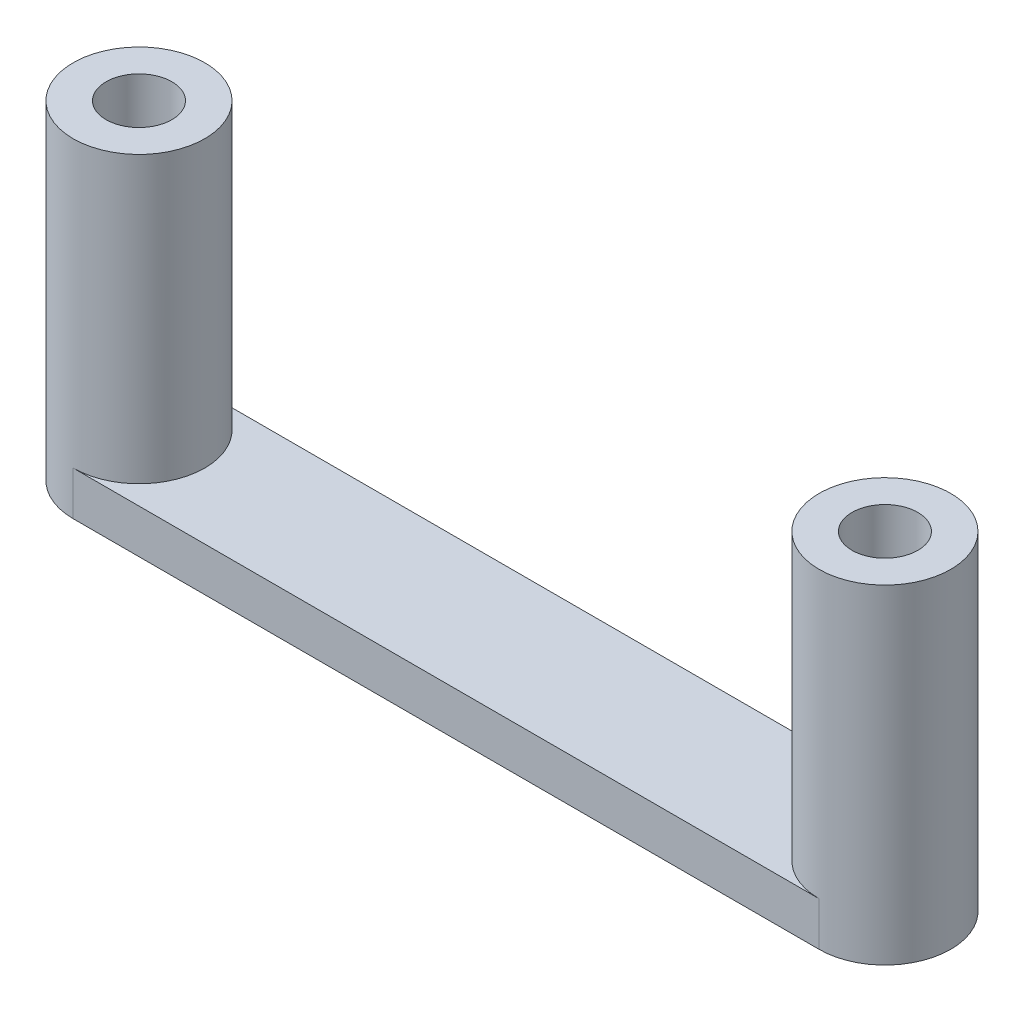
SolidWorks part; units mm, degrees
ref_plane "前视基准面" through (0, 0, 0) normal (0, 0, 1) x (1, 0, 0)
ref_plane "上视基准面" through (0, 0, 0) normal (0, 1, 0) x (1, 0, 0)
ref_plane "右视基准面" through (0, 0, 0) normal (1, 0, 0) x (0, 0, -1)
other "Configuration Table"
sketch "草图1" plane through (0, 0, 0) normal (0, 1, 0) x (1, 0, 0)
  line L0 (-15.9188, 0) -> (18.0812, 0) construction
  line L1 (-15.9188, 3) -> (18.0812, 3)
  line L2 (-15.9188, -3) -> (18.0812, -3)
  arc A0 (-15.9188, 3) -> (-15.9188, -3) centre (-15.9188, 0) ccw
  arc A1 (18.0812, -3) -> (18.0812, 3) centre (18.0812, 0) ccw
  point P3 (1.0812, 0)
  dimension "D1" = 3
  dimension "D2" = 34
extrude "凸台-拉伸1" add sketch "草图1" along normal blind 2
sketch "草图2" plane through (0, 2, 0) normal (0, 1, 0) x (1, 0, 0)
  line L2 (-15.9188, -3) -> (18.0812, -3)
  line L3 (18.0812, 3) -> (-15.9188, 3)
  line L4 (-15.9188, -3) -> (18.0812, -3)
  line L5 (18.0812, 3) -> (-15.9188, 3)
  circle A0 centre (-15.9188, 0) radius 3
  circle A1 centre (18.0812, 0) radius 3
  arc A2 (-15.9188, 3) -> (-15.9188, -3) centre (-15.9188, 0) ccw
  arc A3 (18.0812, -3) -> (18.0812, 3) centre (18.0812, 0) ccw
  arc A4 (-15.9188, 3) -> (-15.9188, -3) centre (-15.9188, 0) ccw
  arc A5 (18.0812, -3) -> (18.0812, 3) centre (18.0812, 0) ccw
  arc M6 (-15.9188, 3) -> (-15.9188, -3) centre (-15.9188, 0) ccw
  arc M8 (18.0812, -3) -> (18.0812, 3) centre (18.0812, 0) ccw
  dimension "D1" = 0
extrude "凸台-拉伸2" add sketch "草图2" along normal blind 13 contours A0 M6 | A1 M8
sketch "草图4" plane through (0, 15, 0) normal (0, 1, 0) x (1, 0, 0)
  circle A0 centre (-15.9188, 0) radius 1.5
  circle A1 centre (-15.9188, 0) radius 3
  circle A2 centre (-15.9188, 0) radius 3
  dimension "D2" = 3
  dimension "D1" = 0
extrude "切除-拉伸1" cut sketch "草图4" against normal through all contours A0
sketch "草图5" plane through (0, 15, 0) normal (0, 1, 0) x (1, 0, 0)
  circle A0 centre (18.0812, 0) radius 1.5
  circle A1 centre (18.0812, 0) radius 3
  circle A2 centre (18.0812, 0) radius 3
  dimension "D2" = 3
  dimension "D1" = 0
extrude "切除-拉伸2" cut sketch "草图5" against normal through all contours A0
